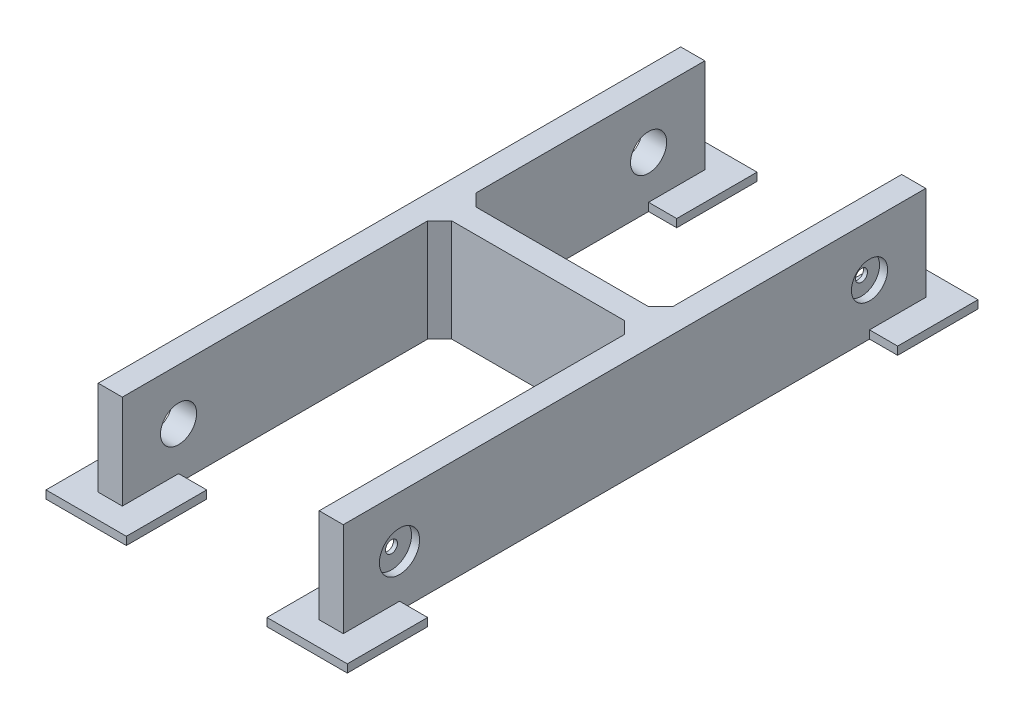
SolidWorks part; units mm, degrees
material "ABS"
ref_plane "Front Plane" through (0, 0, 0) normal (0, 0, 1) x (1, 0, 0)
ref_plane "Top Plane" through (0, 0, 0) normal (0, 1, 0) x (1, 0, 0)
ref_plane "Right Plane" through (0, 0, 0) normal (1, 0, 0) x (0, 0, -1)
other "Center of Mass"
sketch "Sketch1" plane through (0, 0, 0) normal (0, 1, 0) x (1, 0, 0)
  line L12 (6, -6) -> (55, -6)
  line L13 (55, -6) -> (55, -85)
  line L14 (55, -85) -> (61, -85)
  line L15 (61, -85) -> (61, 60)
  line L17 (0, 60) -> (0, -85)
  line L18 (0, -85) -> (6, -85)
  line L19 (6, -85) -> (6, -6)
  line L20 (6, 0) -> (55, 0)
  line L21 (0, 60) -> (6, 60)
  line L22 (6, 60) -> (6, 0)
  line L23 (55, 0) -> (55, 60)
  line L24 (55, 60) -> (61, 60)
  dimension "D1" = 6
  dimension "D2" = 6
  dimension "D3" = 79
  dimension "D4" = 60
  dimension "D5" = 49
extrude "Boss-Extrude1" add sketch "Sketch1" along normal blind 25.5
sketch "Sketch2" plane through (6, 0, 0) normal (1, 0, 0) x (0, 0, -1)
  line L0 (-85, 25.5) -> (-85, 0) construction
  line L2 (-85, 25.5) -> (60, 25.5) construction
  circle A0 centre (-71, 12.75) radius 4.5
  dimension "D2" = 9
  dimension "D3" = 12.75
  dimension "D1" = 14
extrude "Cut-Extrude1" cut sketch "Sketch2" against normal blind 25
sketch "Sketch3" plane through (55, 0, 0) normal (-1, 0, 0) x (0, 0, 1)
  circle A0 centre (71, 12.75) radius 1.5
  dimension "D1" = 3
extrude "Cut-Extrude2" cut sketch "Sketch3" against normal blind 10
sketch "Sketch4" plane through (61, 0, 0) normal (1, 0, 0) x (0, 0, -1)
  circle A0 centre (-71, 12.75) radius 5
  dimension "D1" = 10
extrude "Cut-Extrude3" cut sketch "Sketch4" against normal blind 2
sketch "Sketch5" plane through (55, 0, 0) normal (-1, 0, 0) x (0, 0, 1)
  line L1 (71, 19.25) -> (54, 15.75)
  line L2 (54, 9.75) -> (71, 6.25)
  arc A0 (71, 19.25) -> (71, 6.25) centre (71, 12.75) cw
  circle A1 centre (71, 12.75) radius 5 construction
  arc A2 (54, 15.75) -> (54, 9.75) centre (54, 12.75) ccw
  dimension "D2" = 1.5
  dimension "D1" = 13
  dimension "D3" = 17
  dimension "D4" = 6
extrude "Cut-Extrude4" cut sketch "Sketch5" against normal blind 3
sketch "Sketch6" plane through (55, 0, 0) normal (-1, 0, 0) x (0, 0, 1)
  line L3 (-29, 9.75) -> (-46, 6.25)
  line L4 (-46, 19.25) -> (-29, 15.75)
  line L5 (-60, 25.5) -> (-60, 0) construction
  line L6 (-60, 0) -> (0, 0) construction
  arc A2 (-29, 15.75) -> (-29, 9.75) centre (-29, 12.75) cw
  arc A3 (-46, 19.25) -> (-46, 6.25) centre (-46, 12.75) ccw
  dimension "D1" = 6.5
  dimension "D2" = 3
  dimension "D3" = 14
  dimension "D4" = 17
  dimension "D5" = 12.75
extrude "Cut-Extrude5" cut sketch "Sketch6" against normal blind 3
sketch "Sketch7" plane through (61, 0, 0) normal (1, 0, 0) x (0, 0, -1)
  circle A0 centre (46, 12.75) radius 4.5
  dimension "D1" = 9
extrude "Cut-Extrude6" cut sketch "Sketch7" against normal blind 2
sketch "Sketch8" plane through (61, 0, 0) normal (1, 0, 0) x (0, 0, -1)
  circle A0 centre (46, 12.75) radius 1.5
  dimension "D1" = 3
extrude "Cut-Extrude7" cut sketch "Sketch8" against normal through all both and the other way through all
sketch "Sketch9" plane through (0, 0, 0) normal (-1, 0, 0) x (0, 0, 1)
  circle A0 centre (-46, 12.75) radius 4.5
  dimension "D1" = 9
extrude "Cut-Extrude8" cut sketch "Sketch9" against normal blind 10
sketch "Sketch10" plane through (0, 25.5, 0) normal (0, 1, 0) x (1, 0, 0)
  line L3 (55, 0) -> (6, 0) construction
  line L9 (30.5, 0) -> (30.5, -6) construction
  line L10 (6, -6) -> (55, -6) construction
  line L11 (30.5, -3) -> (37.8663, -3) construction
  line L12 (9, -6) -> (6, -6)
  line L13 (6, -9) -> (9, -6)
  line L14 (6, -6) -> (6, -9)
  line L15 (6, 0) -> (6, 3)
  line L16 (6, 3) -> (9, 0)
  line L17 (9, 0) -> (6, 0)
  line L18 (52, 0) -> (55, 0)
  line L19 (55, 3) -> (52, 0)
  line L20 (55, 0) -> (55, 3)
  line L21 (55, -6) -> (55, -9)
  line L22 (55, -9) -> (52, -6)
  line L23 (52, -6) -> (55, -6)
extrude "Boss-Extrude2" add sketch "Sketch10" against normal up to surface (25.5 mm away) up to face at (30.5, 0, 9.3333)
sketch "Sketch11" plane through (0, 0, 0) normal (0, -1, 0) x (1, 0, 0)
  line L0 (6, -60) -> (0, -60) construction
  line L1 (-7, -46) -> (13, -46)
  line L2 (-7, -46) -> (-7, -66)
  line L3 (-7, -66) -> (13, -66)
  line L4 (13, -46) -> (13, -66)
  line L5 (-7, -46) -> (13, -66) construction
  line L6 (-7, -66) -> (13, -46) construction
  line L7 (0, 85) -> (6, 85) construction
  line L8 (-7, 71) -> (13, 71)
  line L9 (-7, 71) -> (-7, 91)
  line L10 (-7, 91) -> (13, 91)
  line L11 (13, 71) -> (13, 91)
  line L12 (-7, 71) -> (13, 91) construction
  line L13 (-7, 91) -> (13, 71) construction
  line L14 (30.5, 0) -> (30.5, 32.4094) construction
  line L15 (52, 0) -> (9, 0) construction
  line L16 (68, 91) -> (48, 71) construction
  line L17 (68, 71) -> (48, 91) construction
  line L18 (68, -66) -> (48, -46) construction
  line L19 (68, -46) -> (48, -66) construction
  line L20 (48, 71) -> (48, 91)
  line L21 (68, 91) -> (48, 91)
  line L22 (68, 71) -> (68, 91)
  line L23 (68, 71) -> (48, 71)
  line L24 (48, -46) -> (48, -66)
  line L25 (68, -66) -> (48, -66)
  line L26 (68, -46) -> (68, -66)
  line L27 (68, -46) -> (48, -46)
  point P0 (3, -56)
  point P8 (3, -60)
  point P9 (3, 81)
  point P16 (3, 85)
  point P28 (58, 81)
  point P29 (58, -56)
  dimension "D1" = 20
  dimension "D2" = 20
  dimension "D3" = 6
  dimension "D4" = 20
  dimension "D5" = 20
  dimension "D6" = 6
extrude "Boss-Extrude3" add sketch "Sketch11" against normal blind 2
